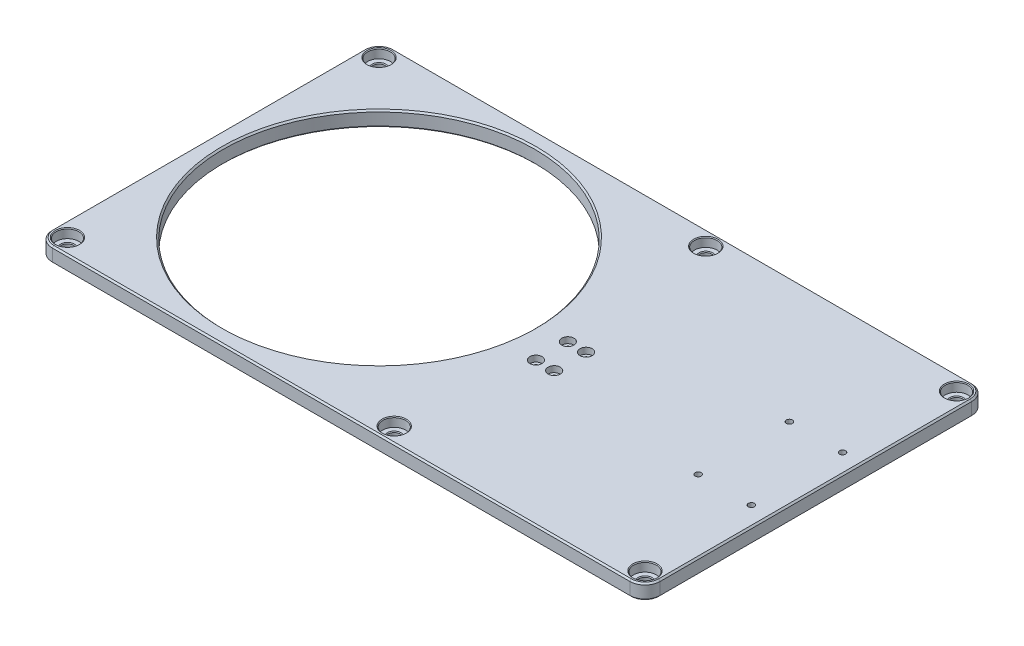
SolidWorks part; units mm, degrees
material "AISI 1020"
ref_plane "Přední rovina" through (0, 0, 0) normal (0, 0, 1) x (1, 0, 0)
ref_plane "Horní rovina" through (0, 0, 0) normal (0, 1, 0) x (1, 0, 0)
ref_plane "Pravá rovina" through (0, 0, 0) normal (1, 0, 0) x (0, 0, -1)
sketch "Skica1" plane through (0, 0, 0) normal (0, 1, 0) x (1, 0, 0)
  line L1 (0, 0) -> (400, 0)
  line L2 (0, 0) -> (0, 225)
  line L3 (0, 225) -> (400, 225)
  line L4 (400, 0) -> (400, 225)
  line L5 (0, 0) -> (400, 225) construction
  line L6 (0, 225) -> (400, 0) construction
  point P4 (200, 112.5)
  dimension "D1" = 225
  dimension "D2" = 400
extrude "Přidat vysunutím1" add sketch "Skica1" along normal blind 10
sketch "Skica2" plane through (0, 10, 0) normal (0, 1, 0) x (1, 0, 0)
  line L0 (0, 225) -> (0, 0) construction
  line L1 (0, 112.5) -> (400, 112.5) construction
  line L2 (400, 0) -> (400, 225) construction
  circle A0 centre (112.5, 112.5) radius 102.5
  dimension "D1" = 205
  dimension "D2" = 112.5
extrude "Odebrat vysunutím1" cut sketch "Skica2" against normal up to surface (10 mm away) up to face at (200, 0, -112.5)
fillet "Zaoblit1" radius 10 4 edges at (400, 5, -225) (400, 5, 0) (0, 5, -225) (0, 5, 0)
sketch "Skica3" plane through (0, 10, 0) normal (0, 1, 0) x (1, 0, 0)
  line L0 (225, 215) -> (225, 10) construction
  circle A0 centre (10, 215) radius 4
  circle A1 centre (390, 215) radius 4
  circle A2 centre (10, 10) radius 4
  circle A3 centre (390, 10) radius 4
  circle A4 centre (225, 215) radius 4
  circle A5 centre (225, 10) radius 4
  dimension "D1" = 8
  dimension "D2" = 8
  dimension "D4" = 8
  dimension "D5" = 8
  dimension "D7" = 215
  dimension "D3" = 2
extrude "Odebrat vysunutím2" cut sketch "Skica3" against normal up to surface (10 mm away) up to face at (112.5, 0, -215)
sketch "Skica4" plane through (0, 10, 0) normal (0, 1, 0) x (1, 0, 0)
  circle A0 centre (10, 215) radius 7.5
  circle A1 centre (390, 215) radius 7.5
  circle A2 centre (10, 10) radius 7.5
  circle A3 centre (390, 10) radius 7.5
  circle A4 centre (225, 215) radius 7.5
  circle A5 centre (225, 10) radius 7.5
  dimension "D1" = 15
  dimension "D2" = 15
  dimension "D4" = 15
  dimension "D5" = 15
  dimension "D3" = 2
extrude "Odebrat vysunutím3" cut sketch "Skica4" against normal blind 6
chamfer "Zkosení1" distance 0.5 angle 45 18 edges at (225, 10, -207.5) (225, 4, -211) (390, 10, -207.5) (390, 4, -211) (390, 10, -2.5) (390, 4, -6) (225, 10, -2.5) (225, 4, -6) (10, 10, -2.5) (10, 4, -6) (10, 4, -211) (10, 10, -207.5) (390, 0, -219) (225, 0, -219) (10, 0, -219) (10, 0, -14) (225, 0, -14) (390, 0, -14)
chamfer "Zkosení2" distance 1 angle 45 2 edges at (112.5, 0, -215) (112.5, 10, -10)
chamfer "Zkosení3" distance 1 angle 45 16 edges at (200, 10, -225) (2.9289, 10, -222.0711) (397.0711, 10, -222.0711) (0, 10, -112.5) (400, 10, -112.5) (2.9289, 10, -2.9289) (397.0711, 10, -2.9289) (200, 10, 0) (200, 0, -225) (2.9289, 0, -222.0711) (397.0711, 0, -222.0711) (0, 0, -112.5) (400, 0, -112.5) (2.9289, 0, -2.9289) (397.0711, 0, -2.9289) (200, 0, 0)
sketch "Skica5" plane through (0, 10, 0) normal (0, 1, 0) x (1, 0, 0)
  line L0 (0, 112.5) -> (400, 112.5) construction
  line L1 (0, 10) -> (0, 215) construction
  line L2 (400, 215) -> (400, 10) construction
  line L4 (352.5, 82.5) -> (387.5, 82.5) construction
  line L5 (352.5, 82.5) -> (352.5, 142.5) construction
  line L6 (352.5, 142.5) -> (387.5, 142.5) construction
  line L7 (387.5, 82.5) -> (387.5, 142.5) construction
  line L8 (352.5, 82.5) -> (387.5, 142.5) construction
  line L9 (352.5, 142.5) -> (387.5, 82.5) construction
  circle A0 centre (352.5, 142.5) radius 2
  circle A1 centre (387.5, 142.5) radius 2
  circle A2 centre (387.5, 82.5) radius 2
  circle A3 centre (352.5, 82.5) radius 2
  point P6 (370, 112.5)
  dimension "D1" = 4
  dimension "D2" = 35
  dimension "D3" = 60
  dimension "D6" = 30
  dimension "D4" = 2
  dimension "D5" = 2
extrude "Odebrat vysunutím4" cut sketch "Skica5" against normal up to surface (10 mm away) up to face at (200, 0, -112.5)
sketch "Skica6" plane through (0, 10, 0) normal (0, 1, 0) x (1, 0, 0)
  line L0 (400, 104.75) -> (0, 104.75) construction
  line L1 (400, 215) -> (400, 10) construction
  line L3 (390, 0) -> (10, 0) construction
  line L4 (234, 94.25) -> (246, 94.25) construction
  line L5 (234, 94.25) -> (234, 115.25) construction
  line L6 (234, 115.25) -> (246, 115.25) construction
  line L7 (246, 94.25) -> (246, 115.25) construction
  line L8 (234, 94.25) -> (246, 115.25) construction
  line L9 (234, 115.25) -> (246, 94.25) construction
  circle A0 centre (234, 115.25) radius 2
  circle A1 centre (246, 115.25) radius 2
  circle A2 centre (246, 94.25) radius 2
  circle A3 centre (234, 94.25) radius 2
  point P6 (240, 104.75)
  dimension "D4" = 4
  dimension "D5" = 4
  dimension "D1" = 160
  dimension "D2" = 12
  dimension "D3" = 21
  dimension "D6" = 104.75
extrude "Odebrat vysunutím5" cut sketch "Skica6" against normal up to surface (10 mm away) up to face at (352.5, 0, -84.5)
sketch "Skica7" plane through (0, 10, 0) normal (0, 1, 0) x (1, 0, 0)
  circle A0 centre (234, 115.25) radius 4
  circle A1 centre (246, 115.25) radius 4
  circle A2 centre (234, 94.25) radius 4
  circle A3 centre (246, 94.25) radius 4
  dimension "D1" = 8
  dimension "D2" = 8
  dimension "D3" = 8
  dimension "D4" = 8
extrude "Odebrat vysunutím6" cut sketch "Skica7" against normal blind 4
